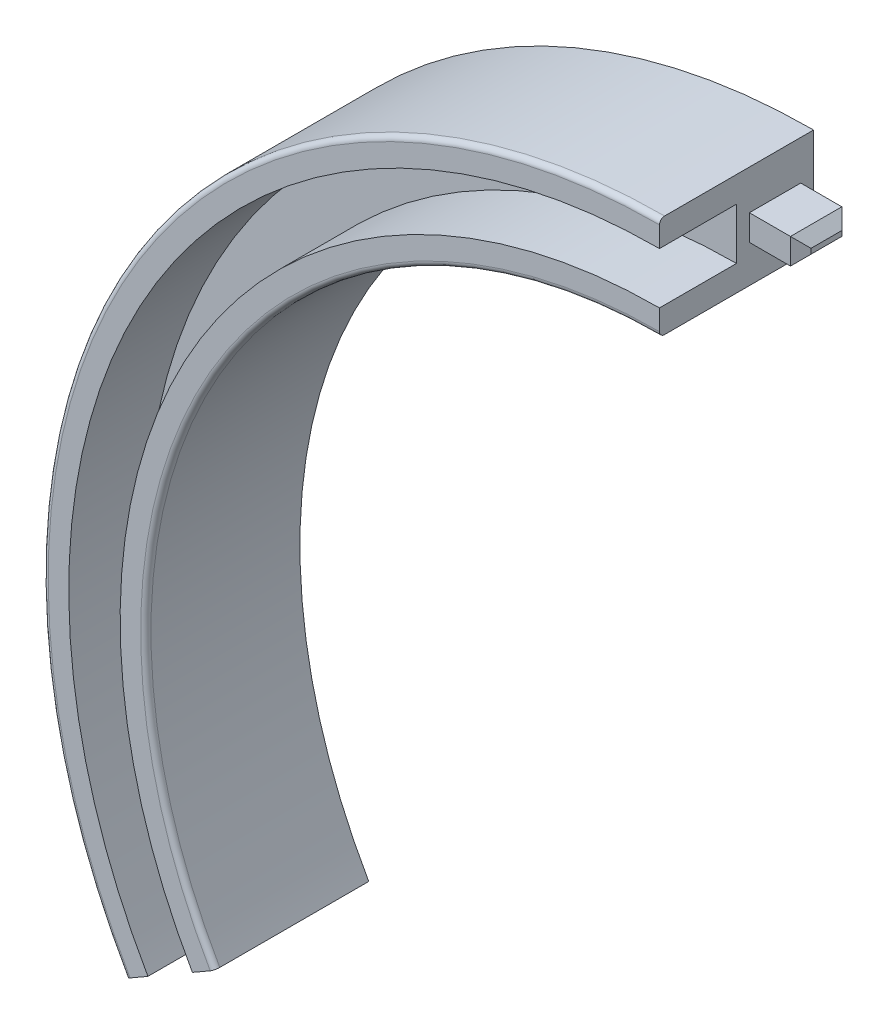
SolidWorks part; units mm, degrees
ref_plane "Alzado" through (0, 0, 0) normal (0, 0, 1) x (1, 0, 0)
ref_plane "Planta" through (0, 0, 0) normal (0, 1, 0) x (1, 0, 0)
ref_plane "Vista lateral" through (0, 0, 0) normal (1, 0, 0) x (0, 0, -1)
sketch "Sketch1" plane through (0, 0, 0) normal (0, 0, 1) x (1, 0, 0)
  line L0 (0, 100) -> (0, 120)
  line L1 (-86.6025, -50) -> (-103.923, -60)
  arc A0 (0, 120) -> (-103.923, -60) centre (0, 0) ccw
  arc A2 (0, 100) -> (-86.6025, -50) centre (0, 0) ccw
  dimension "D1" = 240
  dimension "D3" = 20
  dimension "D2" = 120
extrude "Boss-Extrude2" add sketch "Sketch1" along normal blind 30
sketch "Sketch3" plane through (0, 0, 30) normal (0, 0, 1) x (1, 0, 0)
  line L0 (0, 100) -> (0, 120) construction
  line L1 (-103.923, -60) -> (-86.6025, -50) construction
  line L2 (-99.6372, -57.8081) -> (-90.9327, -52.5)
  line L3 (0, 105) -> (0, 115)
  arc A0 (0, 105) -> (-90.9327, -52.5) centre (0, 0) ccw
  arc A1 (0, 115) -> (-99.5929, -57.5) centre (0, 0) ccw
  dimension "D1" = 5
  dimension "D2" = 10
extrude "Cut-Extrude1" cut sketch "Sketch3" against normal blind 15 and the other way through all
sketch "Sketch4" plane through (0, 0, 0) normal (1, 0, 0) x (0, 0, -1)
  line L2 (-15, 105) -> (-15, 115) construction
  line L3 (-12.5, 112.2983) -> (-2.5, 112.2983)
  line L4 (-12.5, 112.2983) -> (-12.5, 107.2983)
  line L5 (-12.5, 107.2983) -> (-2.5, 107.2983)
  line L6 (-2.5, 112.2983) -> (-2.5, 107.2983)
  line L7 (-12.5, 112.2983) -> (-2.5, 107.2983) construction
  line L8 (-12.5, 107.2983) -> (-2.5, 112.2983) construction
  point P4 (-7.5, 109.7983)
  dimension "D1" = 7.5
  dimension "D2" = 5
  dimension "D3" = 10
extrude "Boss-Extrude3" add sketch "Sketch4" along normal blind 10
chamfer "Chamfer1" distance 2 angle 45 4 edges at (10, 107.2983, 7.5) (10, 109.7983, 12.5) (10, 112.2983, 7.5) (10, 109.7983, 2.5)
sketch "Sketch6" plane through (0, 0, 0) normal (0.5, -0.866, 0) x (0.866, 0.5, 0)
  line L0 (-115, 15) -> (-105, 15) construction
  line L1 (-112.4516, 12.5) -> (-107.4516, 12.5)
  line L2 (-112.4516, 12.5) -> (-112.4516, 2.5)
  line L3 (-112.4516, 2.5) -> (-107.4516, 2.5)
  line L4 (-107.4516, 12.5) -> (-107.4516, 2.5)
  line L5 (-112.4516, 12.5) -> (-107.4516, 2.5) construction
  line L6 (-112.4516, 2.5) -> (-107.4516, 12.5) construction
  point P0 (-109.9516, 7.5)
  dimension "D1" = 7.5
  dimension "D2" = 5
  dimension "D3" = 10
extrude "Cut-Extrude2" cut sketch "Sketch6" against normal blind 10
fillet "Fillet1" radius 1 2 edges at (-103.923, 60, 30) (-86.6025, 50, 30)
